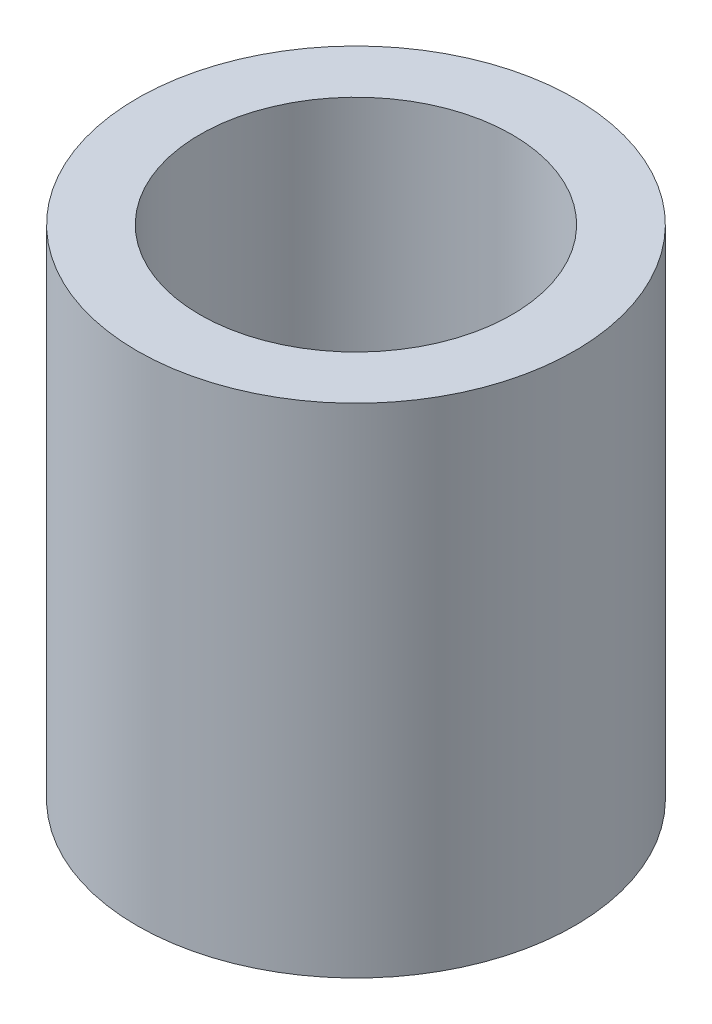
SolidWorks part; units mm, degrees
material "Tin Bearing Bronze"
ref_plane "Front Plane" through (0, 0, 0) normal (0, 0, 1) x (1, 0, 0)
ref_plane "Top Plane" through (0, 0, 0) normal (0, 1, 0) x (1, 0, 0)
ref_plane "Right Plane" through (0, 0, 0) normal (1, 0, 0) x (0, 0, -1)
sketch "Sketch1" plane through (0, 0, 0) normal (0, 1, 0) x (1, 0, 0)
  circle A0 centre (0, 0) radius 5.5816
  circle A1 centre (0, 0) radius 3.9815
  dimension "D1" = 11.1633
  dimension "D2" = 1.6002
extrude "Boss-Extrude1" add sketch "Sketch1" along normal blind 12.7
